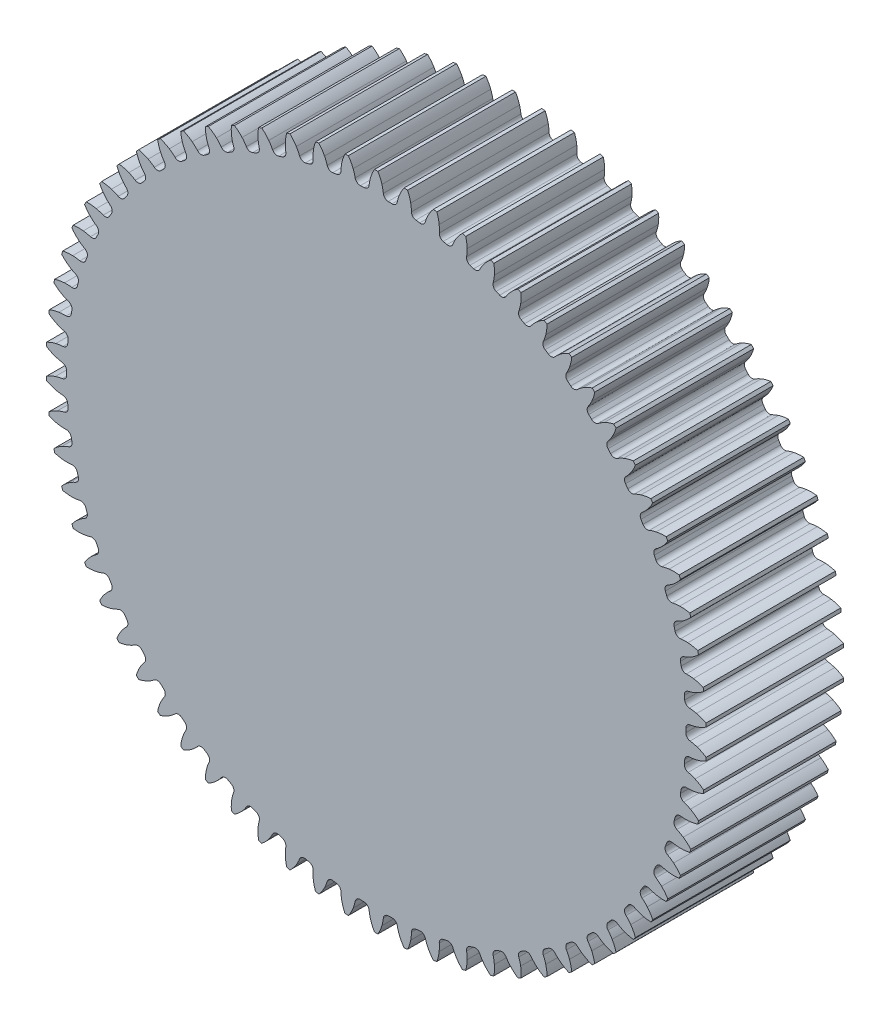
SolidWorks part; units mm, degrees
ref_plane "Front Plane" through (0, 0, 0) normal (0, 0, 1) x (1, 0, 0)
ref_plane "Top Plane" through (0, 0, 0) normal (0, 1, 0) x (1, 0, 0)
ref_plane "Right Plane" through (0, 0, 0) normal (1, 0, 0) x (0, 0, -1)
sketch "Sketch1" plane through (0, 0, 0) normal (0, 0, 1) x (1, 0, 0)
  line L0 (0, 144) -> (0, -144) construction
  circle A0 centre (0, 0) radius 140 construction
  circle A1 centre (0, 0) radius 144 construction
  arc A2 (-5.2094, 134.8995) -> (-6.9038, 134.8234) centre (0, 0) ccw
  arc A3 (-0.75, 143.998) -> (0.75, 143.998) centre (0, 0) cw
  arc A4 (0.75, 143.998) -> (2.5, 139.9777) centre (-13.7397, 135.2999) cw
  arc A5 (2.5, 139.9777) -> (3.1064, 136.8679) centre (-14.8448, 134.9815) cw
  arc A6 (3.1064, 136.8679) -> (5.2094, 134.8995) centre (5.2943, 137.0978) ccw
  arc A7 (-0.75, 143.998) -> (-2.5, 139.9777) centre (13.7397, 135.2999) ccw
  arc A8 (-2.5, 139.9777) -> (-3.1064, 136.8679) centre (14.8448, 134.9815) ccw
  arc A9 (-3.1064, 136.8679) -> (-5.2094, 134.8995) centre (-5.2943, 137.0978) cw
  arc A10 (15.3626, 136.0385) -> (17.2808, 133.8894) centre (17.5624, 136.0713) ccw
  arc A11 (15.0374, 139.1901) -> (15.3626, 136.0385) centre (-2.6854, 135.7688) cw
  arc A12 (12.1609, 143.4856) -> (13.6549, 143.3511) centre (0, 0) cw
  arc A13 (12.1609, 143.4856) -> (10.0576, 139.6383) centre (25.8126, 133.5236) ccw
  arc A14 (10.0576, 139.6383) -> (9.1749, 136.5954) centre (26.8847, 133.1075) ccw
  arc A15 (9.1749, 136.5954) -> (6.9038, 134.8234) centre (7.0163, 137.0205) cw
  arc A16 (13.6549, 143.3511) -> (15.0374, 139.1901) centre (-1.5562, 135.9868) cw
  arc A17 (27.4952, 134.1137) -> (29.213, 131.8014) centre (29.689, 133.9493) ccw
  arc A18 (27.4538, 137.2818) -> (27.4952, 134.1137) centre (9.4957, 135.463) cw
  arc A19 (24.9739, 141.8179) -> (26.4498, 141.55) centre (0, 0) cw
  arc A20 (24.9739, 141.8179) -> (22.5342, 138.1746) centre (37.6776, 130.6722) ccw
  arc A21 (22.5342, 138.1746) -> (21.3822, 135.223) centre (38.7081, 130.1617) ccw
  arc A22 (21.3822, 135.223) -> (18.9615, 133.6617) centre (19.2705, 135.8399) cw
  arc A23 (26.4498, 141.55) -> (27.4538, 137.2818) centre (10.6398, 135.5789) cw
  arc A24 (39.4063, 131.1092) -> (40.9099, 128.6522) centre (41.5766, 130.7487) ccw
  arc A25 (39.6491, 134.2682) -> (39.4063, 131.1092) centre (21.6003, 134.0665) cw
  arc A26 (37.5858, 139.0083) -> (39.0318, 138.6092) centre (0, 0) cw
  arc A27 (37.5858, 139.0083) -> (34.8293, 135.5984) centre (49.2393, 126.7688) ccw
  arc A28 (34.8293, 135.5984) -> (33.4175, 132.762) centre (50.2199, 126.1679) ccw
  arc A29 (33.4175, 132.762) -> (30.8665, 131.424) centre (31.3695, 133.5657) cw
  arc A30 (39.0318, 138.6092) -> (39.6491, 134.2682) centre (22.7502, 134.0793) cw
  arc A31 (51.0002, 127.049) -> (52.2775, 124.4671) centre (53.1295, 126.4955) ccw
  arc A32 (51.5252, 130.1735) -> (51.0002, 127.049) centre (33.5309, 131.5905) cw
  arc A33 (49.8951, 135.0795) -> (51.2995, 134.5525) centre (0, 0) cw
  arc A34 (49.8951, 135.0795) -> (46.844, 131.9304) centre (60.4046, 121.8447) ccw
  arc A35 (46.844, 131.9304) -> (45.1836, 129.232) centre (61.3273, 121.1584) ccw
  arc A36 (45.1836, 129.232) -> (42.523, 128.128) centre (43.216, 130.216) cw
  arc A37 (51.2995, 134.5525) -> (51.5252, 130.1735) centre (34.6774, 131.5002) cw
  arc A38 (62.1835, 121.9659) -> (63.2242, 119.2799) centre (64.2545, 121.2237) ccw
  arc A39 (62.9865, 125.0308) -> (62.1835, 121.9659) centre (45.1916, 128.0551) cw
  arc A40 (61.8027, 130.0632) -> (63.1541, 129.4123) centre (0, 0) cw
  arc A41 (61.8027, 130.0632) -> (58.4816, 127.2002) centre (71.0835, 115.9395) ccw
  arc A42 (58.4816, 127.2002) -> (56.586, 124.6615) centre (71.941, 115.1733) ccw
  arc A43 (56.586, 124.6615) -> (53.8371, 123.8005) centre (54.7145, 125.818) cw
  arc A44 (63.1541, 129.4123) -> (62.9865, 125.0308) centre (46.3254, 127.8624) cw
  arc A45 (72.8661, 115.9008) -> (73.6619, 113.1323) centre (74.8623, 114.976) ccw
  arc A46 (73.9406, 118.8814) -> (72.8661, 115.9008) centre (56.4885, 123.4886) cw
  arc A47 (73.2127, 123.9996) -> (74.5003, 123.2303) centre (0, 0) cw
  arc A48 (73.2127, 123.9996) -> (69.6483, 121.4459) centre (81.19, 109.1009) ccw
  arc A49 (69.6483, 121.4459) -> (67.5328, 119.0873) centre (81.9754, 108.2609) ccw
  arc A50 (67.5328, 119.0873) -> (64.7178, 118.4762) centre (65.7724, 120.4069) cw
  arc A51 (74.5003, 123.2303) -> (73.9406, 118.8814) centre (57.6004, 123.1951) cw
  arc A52 (82.9621, 108.9026) -> (83.5064, 106.0739) centre (84.8673, 107.8025) ccw
  arc A53 (84.2994, 111.7749) -> (82.9621, 108.9026) centre (67.3305, 117.9279) cw
  arc A54 (84.0332, 116.9377) -> (85.2467, 116.056) centre (0, 0) cw
  arc A55 (84.0332, 116.9377) -> (80.2543, 114.7138) centre (90.6429, 101.3839) ccw
  arc A56 (80.2543, 114.7138) -> (77.9358, 112.5543) centre (91.3498, 100.4768) ccw
  arc A57 (77.9358, 112.5543) -> (75.0774, 112.198) centre (76.3009, 114.0264) cw
  arc A58 (85.2467, 116.056) -> (84.2994, 111.7749) centre (68.4116, 117.5359) cw
  arc A59 (92.39, 101.0275) -> (92.6787, 98.1614) centre (94.189, 99.7611) ccw
  arc A60 (93.9794, 103.7683) -> (92.39, 101.0275) centre (77.6304, 111.4177) cw
  arc A61 (94.1771, 108.9343) -> (95.3067, 107.9474) centre (0, 0) cw
  arc A62 (94.1771, 108.9343) -> (90.2141, 107.058) centre (99.366, 92.8506) ccw
  arc A63 (90.2141, 107.058) -> (87.7114, 105.1151) centre (99.9888, 91.8838) ccw
  arc A64 (87.7114, 105.1151) -> (84.8325, 105.0164) centre (86.2149, 106.7278) cw
  arc A65 (95.3067, 107.9474) -> (93.9794, 103.7683) centre (78.672, 110.9303) cw
  arc A66 (101.0741, 92.339) -> (101.1047, 89.4586) centre (102.7523, 90.9165) ccw
  arc A67 (102.9028, 94.9264) -> (101.0741, 92.339) centre (87.3053, 104.0104) cw
  arc A68 (103.5628, 100.0538) -> (104.5993, 98.9696) centre (0, 0) cw
  arc A69 (103.5628, 100.0538) -> (99.4475, 98.5403) centre (107.289, 83.5697) ccw
  arc A70 (99.4475, 98.5403) -> (96.7807, 96.8296) centre (107.8226, 82.551) ccw
  arc A71 (96.7807, 96.8296) -> (93.9046, 96.9893) centre (95.4349, 98.5699) cw
  arc A72 (104.5993, 98.9696) -> (102.9028, 94.9264) centre (88.299, 103.4317) cw
  arc A73 (108.9444, 82.9071) -> (108.7167, 80.0355) centre (110.4884, 81.3398) ccw
  arc A74 (110.9977, 85.3201) -> (108.9444, 82.9071) centre (96.2773, 95.7657) cw
  arc A75 (112.1146, 90.3677) -> (113.0498, 89.1949) centre (0, 0) cw
  arc A76 (112.1146, 90.3677) -> (107.8802, 89.2292) centre (114.3483, 73.6159) ccw
  arc A77 (107.8802, 89.2292) -> (105.0708, 87.7644) centre (114.7884, 72.5535) ccw
  arc A78 (105.0708, 87.7644) -> (102.2206, 88.1813) centre (103.8864, 89.6184) cw
  arc A79 (113.0498, 89.1949) -> (110.9977, 85.3201) centre (97.2151, 95.1002) cw
  arc A80 (115.9376, 72.8076) -> (115.4533, 69.968) centre (117.3348, 71.1083) ccw
  arc A81 (118.1989, 75.0268) -> (115.9376, 72.8076) centre (104.474, 86.75) cw
  arc A82 (119.7637, 79.954) -> (120.5901, 78.7022) centre (0, 0) cw
  arc A83 (119.7637, 79.954) -> (115.4444, 79.1997) centre (120.4868, 63.0695) ccw
  arc A84 (115.4444, 79.1997) -> (112.515, 77.9926) centre (120.8299, 61.9719) ccw
  arc A85 (112.515, 77.9926) -> (109.7136, 78.6634) centre (111.5015, 79.9453) cw
  arc A86 (120.5901, 78.7022) -> (118.1989, 75.0268) centre (105.3485, 86.0031) cw
  arc A87 (121.9973, 62.1219) -> (121.2604, 59.3372) centre (123.2365, 60.3042) ccw
  arc A88 (124.4484, 64.1295) -> (121.9973, 62.1219) centre (111.8297, 77.0358) cw
  arc A89 (126.4486, 68.8966) -> (127.1594, 67.5757) centre (0, 0) cw
  arc A90 (126.4486, 68.8966) -> (122.079, 68.5325) centre (125.6553, 52.0152) ccw
  arc A91 (122.079, 68.5325) -> (119.0532, 67.5929) centre (125.8986, 50.8913) ccw
  arc A92 (119.0532, 67.5929) -> (116.3233, 68.512) centre (118.2189, 69.6285) cw
  arc A93 (127.1594, 67.5757) -> (124.4484, 64.1295) centre (112.6336, 76.2135) cw
  arc A94 (127.0747, 50.9361) -> (126.0912, 48.2286) centre (128.1461, 49.0146) ccw
  arc A95 (129.6959, 52.7159) -> (127.0747, 50.9361) centre (118.2849, 66.7013) cw
  arc A96 (132.1154, 57.2845) -> (132.705, 55.9052) centre (0, 0) cw
  arc A97 (132.1154, 57.2845) -> (127.7308, 57.3136) centre (129.812, 40.5422) ccw
  arc A98 (127.7308, 57.3136) -> (124.6329, 56.6489) centre (129.9537, 39.4009) ccw
  arc A99 (124.6329, 56.6489) -> (121.9963, 57.8091) centre (123.9844, 58.7512) cw
  arc A100 (132.705, 55.9052) -> (129.6959, 52.7159) centre (119.0119, 65.8103) cw
  arc A101 (131.129, 39.3402) -> (129.9068, 36.7317) centre (132.0238, 37.3303) ccw
  arc A102 (133.8992, 40.8778) -> (131.129, 39.3402) centre (123.7878, 55.8298) cw
  arc A103 (136.7185, 45.2111) -> (137.182, 43.7846) centre (0, 0) cw
  arc A104 (136.7185, 45.2111) -> (132.3541, 45.6331) centre (132.9236, 28.7427) ccw
  arc A105 (132.3541, 45.6331) -> (129.2092, 45.2489) centre (132.9624, 27.5934) ccw
  arc A106 (129.2092, 45.2489) -> (126.6872, 46.6407) centre (128.7517, 47.4008) cw
  arc A107 (137.182, 43.7846) -> (133.8992, 40.8778) centre (124.432, 54.8772) cw
  arc A108 (134.1276, 27.4275) -> (132.6765, 24.9391) centre (134.8386, 25.3455) ccw
  arc A109 (137.0244, 28.7106) -> (134.1276, 27.4275) centre (128.294, 44.5088) cw
  arc A110 (140.2208, 32.7738) -> (140.5546, 31.3114) centre (0, 0) cw
  arc A111 (140.2208, 32.7738) -> (135.9118, 33.5853) centre (134.965, 16.7118) ccw
  arc A112 (135.9118, 33.5853) -> (132.7451, 33.4845) centre (134.9006, 15.5636) ccw
  arc A113 (132.7451, 33.4845) -> (130.358, 35.0968) centre (132.4824, 35.6687) cw
  arc A114 (140.5546, 31.3114) -> (137.0244, 28.7106) centre (128.8502, 43.5023) cw
  arc A115 (136.0462, 15.294) -> (134.3779, 12.9457) centre (136.5677, 13.1567) ccw
  arc A116 (139.0464, 16.3123) -> (136.0462, 15.294) centre (131.7673, 32.8294) cw
  arc A117 (142.5942, 20.0725) -> (142.7955, 18.5861) centre (0, 0) cw
  arc A118 (142.5942, 20.0725) -> (138.3753, 21.267) centre (135.9197, 4.5464) ccw
  arc A119 (138.3753, 21.267) -> (135.2122, 21.4505) centre (135.7526, 3.4086) ccw
  arc A120 (135.2122, 21.4505) -> (132.9793, 23.2703) centre (135.1464, 23.6495) cw
  arc A121 (142.7955, 18.5861) -> (139.0464, 16.3123) centre (132.231, 31.7771) cw
  arc A122 (136.8694, 3.0373) -> (134.9973, 0.848) centre (137.1973, 0.8619) ccw
  arc A123 (139.9489, 3.7826) -> (136.8694, 3.0373) centre (134.1796, 20.8858) cw
  arc A124 (143.8194, 7.2097) -> (143.8867, 5.7112) centre (0, 0) cw
  arc A125 (143.8194, 7.2097) -> (139.7246, 8.7776) centre (135.7801, -7.6557) ccw
  arc A126 (139.7246, 8.7776) -> (136.5907, 9.2438) centre (135.5116, -8.7739) ccw
  arc A127 (136.5907, 9.2438) -> (134.5299, 11.2564) centre (136.7222, 11.4399) cw
  arc A128 (143.8867, 5.7112) -> (139.9489, 3.7826) centre (134.5472, 19.7961) cw
  arc A129 (136.5907, -9.2438) -> (134.5299, -11.2564) centre (136.7222, -11.4399) ccw
  arc A130 (139.7246, -8.7776) -> (136.5907, -9.2438) centre (135.5116, 8.7739) cw
  arc A131 (143.8867, -5.7112) -> (143.8194, -7.2097) centre (0, 0) cw
  arc A132 (143.8867, -5.7112) -> (139.9489, -3.7826) centre (134.5472, -19.7961) ccw
  arc A133 (139.9489, -3.7826) -> (136.8694, -3.0373) centre (134.1796, -20.8858) ccw
  arc A134 (136.8694, -3.0373) -> (134.9973, -0.848) centre (137.1973, -0.8619) cw
  arc A135 (143.8194, -7.2097) -> (139.7246, -8.7776) centre (135.7801, 7.6557) cw
  arc A136 (135.2122, -21.4505) -> (132.9793, -23.2703) centre (135.1464, -23.6495) ccw
  arc A137 (138.3753, -21.267) -> (135.2122, -21.4505) centre (135.7526, -3.4086) cw
  arc A138 (142.7955, -18.5861) -> (142.5942, -20.0725) centre (0, 0) cw
  arc A139 (142.7955, -18.5861) -> (139.0464, -16.3123) centre (132.231, -31.7771) ccw
  arc A140 (139.0464, -16.3123) -> (136.0462, -15.294) centre (131.7673, -32.8294) ccw
  arc A141 (136.0462, -15.294) -> (134.3779, -12.9457) centre (136.5677, -13.1567) cw
  arc A142 (142.5942, -20.0725) -> (138.3753, -21.267) centre (135.9197, -4.5464) cw
  arc A143 (132.7451, -33.4845) -> (130.358, -35.0968) centre (132.4824, -35.6687) ccw
  arc A144 (135.9118, -33.5853) -> (132.7451, -33.4845) centre (134.9006, -15.5636) cw
  arc A145 (140.5546, -31.3114) -> (140.2208, -32.7738) centre (0, 0) cw
  arc A146 (140.5546, -31.3114) -> (137.0244, -28.7106) centre (128.8502, -43.5023) ccw
  arc A147 (137.0244, -28.7106) -> (134.1276, -27.4275) centre (128.294, -44.5088) ccw
  arc A148 (134.1276, -27.4275) -> (132.6765, -24.9391) centre (134.8386, -25.3455) cw
  arc A149 (140.2208, -32.7738) -> (135.9118, -33.5853) centre (134.965, -16.7118) cw
  arc A150 (129.2092, -45.2489) -> (126.6872, -46.6407) centre (128.7517, -47.4008) ccw
  arc A151 (132.3541, -45.6331) -> (129.2092, -45.2489) centre (132.9624, -27.5934) cw
  arc A152 (137.182, -43.7846) -> (136.7185, -45.2111) centre (0, 0) cw
  arc A153 (137.182, -43.7846) -> (133.8992, -40.8778) centre (124.432, -54.8772) ccw
  arc A154 (133.8992, -40.8778) -> (131.129, -39.3402) centre (123.7878, -55.8298) ccw
  arc A155 (131.129, -39.3402) -> (129.9068, -36.7317) centre (132.0238, -37.3303) cw
  arc A156 (136.7185, -45.2111) -> (132.3541, -45.6331) centre (132.9236, -28.7427) cw
  arc A157 (124.6329, -56.6489) -> (121.9963, -57.8091) centre (123.9844, -58.7512) ccw
  arc A158 (127.7308, -57.3136) -> (124.6329, -56.6489) centre (129.9537, -39.4009) cw
  arc A159 (132.705, -55.9052) -> (132.1154, -57.2845) centre (0, 0) cw
  arc A160 (132.705, -55.9052) -> (129.6959, -52.7159) centre (119.0119, -65.8103) ccw
  arc A161 (129.6959, -52.7159) -> (127.0747, -50.9361) centre (118.2849, -66.7013) ccw
  arc A162 (127.0747, -50.9361) -> (126.0912, -48.2286) centre (128.1461, -49.0146) cw
  arc A163 (132.1154, -57.2845) -> (127.7308, -57.3136) centre (129.812, -40.5422) cw
  arc A164 (119.0532, -67.5929) -> (116.3233, -68.512) centre (118.2189, -69.6285) ccw
  arc A165 (122.079, -68.5325) -> (119.0532, -67.5929) centre (125.8986, -50.8913) cw
  arc A166 (127.1594, -67.5757) -> (126.4486, -68.8966) centre (0, 0) cw
  arc A167 (127.1594, -67.5757) -> (124.4484, -64.1295) centre (112.6336, -76.2135) ccw
  arc A168 (124.4484, -64.1295) -> (121.9973, -62.1219) centre (111.8297, -77.0358) ccw
  arc A169 (121.9973, -62.1219) -> (121.2604, -59.3372) centre (123.2365, -60.3042) cw
  arc A170 (126.4486, -68.8966) -> (122.079, -68.5325) centre (125.6553, -52.0152) cw
  arc A171 (112.515, -77.9926) -> (109.7136, -78.6634) centre (111.5015, -79.9453) ccw
  arc A172 (115.4444, -79.1997) -> (112.515, -77.9926) centre (120.8299, -61.9719) cw
  arc A173 (120.5901, -78.7022) -> (119.7637, -79.954) centre (0, 0) cw
  arc A174 (120.5901, -78.7022) -> (118.1989, -75.0268) centre (105.3485, -86.0031) ccw
  arc A175 (118.1989, -75.0268) -> (115.9376, -72.8076) centre (104.474, -86.75) ccw
  arc A176 (115.9376, -72.8076) -> (115.4533, -69.968) centre (117.3348, -71.1083) cw
  arc A177 (119.7637, -79.954) -> (115.4444, -79.1997) centre (120.4868, -63.0695) cw
  arc A178 (105.0708, -87.7644) -> (102.2206, -88.1813) centre (103.8864, -89.6184) ccw
  arc A179 (107.8802, -89.2292) -> (105.0708, -87.7644) centre (114.7884, -72.5535) cw
  arc A180 (113.0498, -89.1949) -> (112.1146, -90.3677) centre (0, 0) cw
  arc A181 (113.0498, -89.1949) -> (110.9977, -85.3201) centre (97.2151, -95.1002) ccw
  arc A182 (110.9977, -85.3201) -> (108.9444, -82.9071) centre (96.2773, -95.7657) ccw
  arc A183 (108.9444, -82.9071) -> (108.7167, -80.0355) centre (110.4884, -81.3398) cw
  arc A184 (112.1146, -90.3677) -> (107.8802, -89.2292) centre (114.3483, -73.6159) cw
  arc A185 (96.7807, -96.8296) -> (93.9046, -96.9893) centre (95.4349, -98.5699) ccw
  arc A186 (99.4475, -98.5403) -> (96.7807, -96.8296) centre (107.8226, -82.551) cw
  arc A187 (104.5993, -98.9696) -> (103.5628, -100.0538) centre (0, 0) cw
  arc A188 (104.5993, -98.9696) -> (102.9028, -94.9264) centre (88.299, -103.4317) ccw
  arc A189 (102.9028, -94.9264) -> (101.0741, -92.339) centre (87.3053, -104.0104) ccw
  arc A190 (101.0741, -92.339) -> (101.1047, -89.4586) centre (102.7523, -90.9165) cw
  arc A191 (103.5628, -100.0538) -> (99.4475, -98.5403) centre (107.289, -83.5697) cw
  arc A192 (87.7114, -105.1151) -> (84.8325, -105.0164) centre (86.2149, -106.7278) ccw
  arc A193 (90.2141, -107.058) -> (87.7114, -105.1151) centre (99.9888, -91.8838) cw
  arc A194 (95.3067, -107.9474) -> (94.1771, -108.9343) centre (0, 0) cw
  arc A195 (95.3067, -107.9474) -> (93.9794, -103.7683) centre (78.672, -110.9303) ccw
  arc A196 (93.9794, -103.7683) -> (92.39, -101.0275) centre (77.6304, -111.4177) ccw
  arc A197 (92.39, -101.0275) -> (92.6787, -98.1614) centre (94.189, -99.7611) cw
  arc A198 (94.1771, -108.9343) -> (90.2141, -107.058) centre (99.366, -92.8506) cw
  arc A199 (77.9358, -112.5543) -> (75.0774, -112.198) centre (76.3009, -114.0264) ccw
  arc A200 (80.2543, -114.7138) -> (77.9358, -112.5543) centre (91.3498, -100.4768) cw
  arc A201 (85.2467, -116.056) -> (84.0332, -116.9377) centre (0, 0) cw
  arc A202 (85.2467, -116.056) -> (84.2994, -111.7749) centre (68.4116, -117.5359) ccw
  arc A203 (84.2994, -111.7749) -> (82.9621, -108.9026) centre (67.3305, -117.9279) ccw
  arc A204 (82.9621, -108.9026) -> (83.5064, -106.0739) centre (84.8673, -107.8025) cw
  arc A205 (84.0332, -116.9377) -> (80.2543, -114.7138) centre (90.6429, -101.3839) cw
  arc A206 (67.5328, -119.0873) -> (64.7178, -118.4762) centre (65.7724, -120.4069) ccw
  arc A207 (69.6483, -121.4459) -> (67.5328, -119.0873) centre (81.9754, -108.2609) cw
  arc A208 (74.5003, -123.2303) -> (73.2127, -123.9996) centre (0, 0) cw
  arc A209 (74.5003, -123.2303) -> (73.9406, -118.8814) centre (57.6004, -123.1951) ccw
  arc A210 (73.9406, -118.8814) -> (72.8661, -115.9008) centre (56.4885, -123.4886) ccw
  arc A211 (72.8661, -115.9008) -> (73.6619, -113.1323) centre (74.8623, -114.976) cw
  arc A212 (73.2127, -123.9996) -> (69.6483, -121.4459) centre (81.19, -109.1009) cw
  arc A213 (56.586, -124.6615) -> (53.8371, -123.8005) centre (54.7145, -125.818) ccw
  arc A214 (58.4816, -127.2002) -> (56.586, -124.6615) centre (71.941, -115.1733) cw
  arc A215 (63.1541, -129.4123) -> (61.8027, -130.0632) centre (0, 0) cw
  arc A216 (63.1541, -129.4123) -> (62.9865, -125.0308) centre (46.3254, -127.8624) ccw
  arc A217 (62.9865, -125.0308) -> (62.1835, -121.9659) centre (45.1916, -128.0551) ccw
  arc A218 (62.1835, -121.9659) -> (63.2242, -119.2799) centre (64.2545, -121.2237) cw
  arc A219 (61.8027, -130.0632) -> (58.4816, -127.2002) centre (71.0835, -115.9395) cw
  arc A220 (45.1836, -129.232) -> (42.523, -128.128) centre (43.216, -130.216) ccw
  arc A221 (46.844, -131.9304) -> (45.1836, -129.232) centre (61.3273, -121.1584) cw
  arc A222 (51.2995, -134.5525) -> (49.8951, -135.0795) centre (0, 0) cw
  arc A223 (51.2995, -134.5525) -> (51.5252, -130.1735) centre (34.6774, -131.5002) ccw
  arc A224 (51.5252, -130.1735) -> (51.0002, -127.049) centre (33.5309, -131.5905) ccw
  arc A225 (51.0002, -127.049) -> (52.2775, -124.4671) centre (53.1295, -126.4955) cw
  arc A226 (49.8951, -135.0795) -> (46.844, -131.9304) centre (60.4046, -121.8447) cw
  arc A227 (33.4175, -132.762) -> (30.8665, -131.424) centre (31.3695, -133.5657) ccw
  arc A228 (34.8293, -135.5984) -> (33.4175, -132.762) centre (50.2199, -126.1679) cw
  arc A229 (39.0318, -138.6092) -> (37.5858, -139.0083) centre (0, 0) cw
  arc A230 (39.0318, -138.6092) -> (39.6491, -134.2682) centre (22.7502, -134.0793) ccw
  arc A231 (39.6491, -134.2682) -> (39.4063, -131.1092) centre (21.6003, -134.0665) ccw
  arc A232 (39.4063, -131.1092) -> (40.9099, -128.6522) centre (41.5766, -130.7487) cw
  arc A233 (37.5858, -139.0083) -> (34.8293, -135.5984) centre (49.2393, -126.7688) cw
  arc A234 (21.3822, -135.223) -> (18.9615, -133.6617) centre (19.2705, -135.8399) ccw
  arc A235 (22.5342, -138.1746) -> (21.3822, -135.223) centre (38.7081, -130.1617) cw
  arc A236 (26.4498, -141.55) -> (24.9739, -141.8179) centre (0, 0) cw
  arc A237 (26.4498, -141.55) -> (27.4538, -137.2818) centre (10.6398, -135.5789) ccw
  arc A238 (27.4538, -137.2818) -> (27.4952, -134.1137) centre (9.4957, -135.463) ccw
  arc A239 (27.4952, -134.1137) -> (29.213, -131.8014) centre (29.689, -133.9493) cw
  arc A240 (24.9739, -141.8179) -> (22.5342, -138.1746) centre (37.6776, -130.6722) cw
  arc A241 (9.1749, -136.5954) -> (6.9038, -134.8234) centre (7.0163, -137.0205) ccw
  arc A242 (10.0576, -139.6383) -> (9.1749, -136.5954) centre (26.8847, -133.1075) cw
  arc A243 (13.6549, -143.3511) -> (12.1609, -143.4856) centre (0, 0) cw
  arc A244 (13.6549, -143.3511) -> (15.0374, -139.1901) centre (-1.5562, -135.9868) ccw
  arc A245 (15.0374, -139.1901) -> (15.3626, -136.0385) centre (-2.6854, -135.7688) ccw
  arc A246 (15.3626, -136.0385) -> (17.2808, -133.8894) centre (17.5624, -136.0713) cw
  arc A247 (12.1609, -143.4856) -> (10.0576, -139.6383) centre (25.8126, -133.5236) cw
  arc A248 (-3.1064, -136.8679) -> (-5.2094, -134.8995) centre (-5.2943, -137.0978) ccw
  arc A249 (-2.5, -139.9777) -> (-3.1064, -136.8679) centre (14.8448, -134.9815) cw
  arc A250 (0.75, -143.998) -> (-0.75, -143.998) centre (0, 0) cw
  arc A251 (0.75, -143.998) -> (2.5, -139.9777) centre (-13.7397, -135.2999) ccw
  arc A252 (2.5, -139.9777) -> (3.1064, -136.8679) centre (-14.8448, -134.9815) ccw
  arc A253 (3.1064, -136.8679) -> (5.2094, -134.8995) centre (5.2943, -137.0978) cw
  arc A254 (-0.75, -143.998) -> (-2.5, -139.9777) centre (13.7397, -135.2999) cw
  arc A255 (-15.3626, -136.0385) -> (-17.2808, -133.8894) centre (-17.5624, -136.0713) ccw
  arc A256 (-15.0374, -139.1901) -> (-15.3626, -136.0385) centre (2.6854, -135.7688) cw
  arc A257 (-12.1609, -143.4856) -> (-13.6549, -143.3511) centre (0, 0) cw
  arc A258 (-12.1609, -143.4856) -> (-10.0576, -139.6383) centre (-25.8126, -133.5236) ccw
  arc A259 (-10.0576, -139.6383) -> (-9.1749, -136.5954) centre (-26.8847, -133.1075) ccw
  arc A260 (-9.1749, -136.5954) -> (-6.9038, -134.8234) centre (-7.0163, -137.0205) cw
  arc A261 (-13.6549, -143.3511) -> (-15.0374, -139.1901) centre (1.5562, -135.9868) cw
  arc A262 (-27.4952, -134.1137) -> (-29.213, -131.8014) centre (-29.689, -133.9493) ccw
  arc A263 (-27.4538, -137.2818) -> (-27.4952, -134.1137) centre (-9.4957, -135.463) cw
  arc A264 (-24.9739, -141.8179) -> (-26.4498, -141.55) centre (0, 0) cw
  arc A265 (-24.9739, -141.8179) -> (-22.5342, -138.1746) centre (-37.6776, -130.6722) ccw
  arc A266 (-22.5342, -138.1746) -> (-21.3822, -135.223) centre (-38.7081, -130.1617) ccw
  arc A267 (-21.3822, -135.223) -> (-18.9615, -133.6617) centre (-19.2705, -135.8399) cw
  arc A268 (-26.4498, -141.55) -> (-27.4538, -137.2818) centre (-10.6398, -135.5789) cw
  arc A269 (-39.4063, -131.1092) -> (-40.9099, -128.6522) centre (-41.5766, -130.7487) ccw
  arc A270 (-39.6491, -134.2682) -> (-39.4063, -131.1092) centre (-21.6003, -134.0665) cw
  arc A271 (-37.5858, -139.0083) -> (-39.0318, -138.6092) centre (0, 0) cw
  arc A272 (-37.5858, -139.0083) -> (-34.8293, -135.5984) centre (-49.2393, -126.7688) ccw
  arc A273 (-34.8293, -135.5984) -> (-33.4175, -132.762) centre (-50.2199, -126.1679) ccw
  arc A274 (-33.4175, -132.762) -> (-30.8665, -131.424) centre (-31.3695, -133.5657) cw
  arc A275 (-39.0318, -138.6092) -> (-39.6491, -134.2682) centre (-22.7502, -134.0793) cw
  arc A276 (-51.0002, -127.049) -> (-52.2775, -124.4671) centre (-53.1295, -126.4955) ccw
  arc A277 (-51.5252, -130.1735) -> (-51.0002, -127.049) centre (-33.5309, -131.5905) cw
  arc A278 (-49.8951, -135.0795) -> (-51.2995, -134.5525) centre (0, 0) cw
  arc A279 (-49.8951, -135.0795) -> (-46.844, -131.9304) centre (-60.4046, -121.8447) ccw
  arc A280 (-46.844, -131.9304) -> (-45.1836, -129.232) centre (-61.3273, -121.1584) ccw
  arc A281 (-45.1836, -129.232) -> (-42.523, -128.128) centre (-43.216, -130.216) cw
  arc A282 (-51.2995, -134.5525) -> (-51.5252, -130.1735) centre (-34.6774, -131.5002) cw
  arc A283 (-62.1835, -121.9659) -> (-63.2242, -119.2799) centre (-64.2545, -121.2237) ccw
  arc A284 (-62.9865, -125.0308) -> (-62.1835, -121.9659) centre (-45.1916, -128.0551) cw
  arc A285 (-61.8027, -130.0632) -> (-63.1541, -129.4123) centre (0, 0) cw
  arc A286 (-61.8027, -130.0632) -> (-58.4816, -127.2002) centre (-71.0835, -115.9395) ccw
  arc A287 (-58.4816, -127.2002) -> (-56.586, -124.6615) centre (-71.941, -115.1733) ccw
  arc A288 (-56.586, -124.6615) -> (-53.8371, -123.8005) centre (-54.7145, -125.818) cw
  arc A289 (-63.1541, -129.4123) -> (-62.9865, -125.0308) centre (-46.3254, -127.8624) cw
  arc A290 (-72.8661, -115.9008) -> (-73.6619, -113.1323) centre (-74.8623, -114.976) ccw
  arc A291 (-73.9406, -118.8814) -> (-72.8661, -115.9008) centre (-56.4885, -123.4886) cw
  arc A292 (-73.2127, -123.9996) -> (-74.5003, -123.2303) centre (0, 0) cw
  arc A293 (-73.2127, -123.9996) -> (-69.6483, -121.4459) centre (-81.19, -109.1009) ccw
  arc A294 (-69.6483, -121.4459) -> (-67.5328, -119.0873) centre (-81.9754, -108.2609) ccw
  arc A295 (-67.5328, -119.0873) -> (-64.7178, -118.4762) centre (-65.7724, -120.4069) cw
  arc A296 (-74.5003, -123.2303) -> (-73.9406, -118.8814) centre (-57.6004, -123.1951) cw
  arc A297 (-82.9621, -108.9026) -> (-83.5064, -106.0739) centre (-84.8673, -107.8025) ccw
  arc A298 (-84.2994, -111.7749) -> (-82.9621, -108.9026) centre (-67.3305, -117.9279) cw
  arc A299 (-84.0332, -116.9377) -> (-85.2467, -116.056) centre (0, 0) cw
  arc A300 (-84.0332, -116.9377) -> (-80.2543, -114.7138) centre (-90.6429, -101.3839) ccw
  arc A301 (-80.2543, -114.7138) -> (-77.9358, -112.5543) centre (-91.3498, -100.4768) ccw
  arc A302 (-77.9358, -112.5543) -> (-75.0774, -112.198) centre (-76.3009, -114.0264) cw
  arc A303 (-85.2467, -116.056) -> (-84.2994, -111.7749) centre (-68.4116, -117.5359) cw
  arc A304 (-92.39, -101.0275) -> (-92.6787, -98.1614) centre (-94.189, -99.7611) ccw
  arc A305 (-93.9794, -103.7683) -> (-92.39, -101.0275) centre (-77.6304, -111.4177) cw
  arc A306 (-94.1771, -108.9343) -> (-95.3067, -107.9474) centre (0, 0) cw
  arc A307 (-94.1771, -108.9343) -> (-90.2141, -107.058) centre (-99.366, -92.8506) ccw
  arc A308 (-90.2141, -107.058) -> (-87.7114, -105.1151) centre (-99.9888, -91.8838) ccw
  arc A309 (-87.7114, -105.1151) -> (-84.8325, -105.0164) centre (-86.2149, -106.7278) cw
  arc A310 (-95.3067, -107.9474) -> (-93.9794, -103.7683) centre (-78.672, -110.9303) cw
  arc A311 (-101.0741, -92.339) -> (-101.1047, -89.4586) centre (-102.7523, -90.9165) ccw
  arc A312 (-102.9028, -94.9264) -> (-101.0741, -92.339) centre (-87.3053, -104.0104) cw
  arc A313 (-103.5628, -100.0538) -> (-104.5993, -98.9696) centre (0, 0) cw
  arc A314 (-103.5628, -100.0538) -> (-99.4475, -98.5403) centre (-107.289, -83.5697) ccw
  arc A315 (-99.4475, -98.5403) -> (-96.7807, -96.8296) centre (-107.8226, -82.551) ccw
  arc A316 (-96.7807, -96.8296) -> (-93.9046, -96.9893) centre (-95.4349, -98.5699) cw
  arc A317 (-104.5993, -98.9696) -> (-102.9028, -94.9264) centre (-88.299, -103.4317) cw
  arc A318 (-108.9444, -82.9071) -> (-108.7167, -80.0355) centre (-110.4884, -81.3398) ccw
  arc A319 (-110.9977, -85.3201) -> (-108.9444, -82.9071) centre (-96.2773, -95.7657) cw
  arc A320 (-112.1146, -90.3677) -> (-113.0498, -89.1949) centre (0, 0) cw
  arc A321 (-112.1146, -90.3677) -> (-107.8802, -89.2292) centre (-114.3483, -73.6159) ccw
  arc A322 (-107.8802, -89.2292) -> (-105.0708, -87.7644) centre (-114.7884, -72.5535) ccw
  arc A323 (-105.0708, -87.7644) -> (-102.2206, -88.1813) centre (-103.8864, -89.6184) cw
  arc A324 (-113.0498, -89.1949) -> (-110.9977, -85.3201) centre (-97.2151, -95.1002) cw
  arc A325 (-115.9376, -72.8076) -> (-115.4533, -69.968) centre (-117.3348, -71.1083) ccw
  arc A326 (-118.1989, -75.0268) -> (-115.9376, -72.8076) centre (-104.474, -86.75) cw
  arc A327 (-119.7637, -79.954) -> (-120.5901, -78.7022) centre (0, 0) cw
  arc A328 (-119.7637, -79.954) -> (-115.4444, -79.1997) centre (-120.4868, -63.0695) ccw
  arc A329 (-115.4444, -79.1997) -> (-112.515, -77.9926) centre (-120.8299, -61.9719) ccw
  arc A330 (-112.515, -77.9926) -> (-109.7136, -78.6634) centre (-111.5015, -79.9453) cw
  arc A331 (-120.5901, -78.7022) -> (-118.1989, -75.0268) centre (-105.3485, -86.0031) cw
  arc A332 (-121.9973, -62.1219) -> (-121.2604, -59.3372) centre (-123.2365, -60.3042) ccw
  arc A333 (-124.4484, -64.1295) -> (-121.9973, -62.1219) centre (-111.8297, -77.0358) cw
  arc A334 (-126.4486, -68.8966) -> (-127.1594, -67.5757) centre (0, 0) cw
  arc A335 (-126.4486, -68.8966) -> (-122.079, -68.5325) centre (-125.6553, -52.0152) ccw
  arc A336 (-122.079, -68.5325) -> (-119.0532, -67.5929) centre (-125.8986, -50.8913) ccw
  arc A337 (-119.0532, -67.5929) -> (-116.3233, -68.512) centre (-118.2189, -69.6285) cw
  arc A338 (-127.1594, -67.5757) -> (-124.4484, -64.1295) centre (-112.6336, -76.2135) cw
  arc A339 (-127.0747, -50.9361) -> (-126.0912, -48.2286) centre (-128.1461, -49.0146) ccw
  arc A340 (-129.6959, -52.7159) -> (-127.0747, -50.9361) centre (-118.2849, -66.7013) cw
  arc A341 (-132.1154, -57.2845) -> (-132.705, -55.9052) centre (0, 0) cw
  arc A342 (-132.1154, -57.2845) -> (-127.7308, -57.3136) centre (-129.812, -40.5422) ccw
  arc A343 (-127.7308, -57.3136) -> (-124.6329, -56.6489) centre (-129.9537, -39.4009) ccw
  arc A344 (-124.6329, -56.6489) -> (-121.9963, -57.8091) centre (-123.9844, -58.7512) cw
  arc A345 (-132.705, -55.9052) -> (-129.6959, -52.7159) centre (-119.0119, -65.8103) cw
  arc A346 (-131.129, -39.3402) -> (-129.9068, -36.7317) centre (-132.0238, -37.3303) ccw
  arc A347 (-133.8992, -40.8778) -> (-131.129, -39.3402) centre (-123.7878, -55.8298) cw
  arc A348 (-136.7185, -45.2111) -> (-137.182, -43.7846) centre (0, 0) cw
  arc A349 (-136.7185, -45.2111) -> (-132.3541, -45.6331) centre (-132.9236, -28.7427) ccw
  arc A350 (-132.3541, -45.6331) -> (-129.2092, -45.2489) centre (-132.9624, -27.5934) ccw
  arc A351 (-129.2092, -45.2489) -> (-126.6872, -46.6407) centre (-128.7517, -47.4008) cw
  arc A352 (-137.182, -43.7846) -> (-133.8992, -40.8778) centre (-124.432, -54.8772) cw
  arc A353 (-134.1276, -27.4275) -> (-132.6765, -24.9391) centre (-134.8386, -25.3455) ccw
  arc A354 (-137.0244, -28.7106) -> (-134.1276, -27.4275) centre (-128.294, -44.5088) cw
  arc A355 (-140.2208, -32.7738) -> (-140.5546, -31.3114) centre (0, 0) cw
  arc A356 (-140.2208, -32.7738) -> (-135.9118, -33.5853) centre (-134.965, -16.7118) ccw
  arc A357 (-135.9118, -33.5853) -> (-132.7451, -33.4845) centre (-134.9006, -15.5636) ccw
  arc A358 (-132.7451, -33.4845) -> (-130.358, -35.0968) centre (-132.4824, -35.6687) cw
  arc A359 (-140.5546, -31.3114) -> (-137.0244, -28.7106) centre (-128.8502, -43.5023) cw
  arc A360 (-136.0462, -15.294) -> (-134.3779, -12.9457) centre (-136.5677, -13.1567) ccw
  arc A361 (-139.0464, -16.3123) -> (-136.0462, -15.294) centre (-131.7673, -32.8294) cw
  arc A362 (-142.5942, -20.0725) -> (-142.7955, -18.5861) centre (0, 0) cw
  arc A363 (-142.5942, -20.0725) -> (-138.3753, -21.267) centre (-135.9197, -4.5464) ccw
  arc A364 (-138.3753, -21.267) -> (-135.2122, -21.4505) centre (-135.7526, -3.4086) ccw
  arc A365 (-135.2122, -21.4505) -> (-132.9793, -23.2703) centre (-135.1464, -23.6495) cw
  arc A366 (-142.7955, -18.5861) -> (-139.0464, -16.3123) centre (-132.231, -31.7771) cw
  arc A367 (-136.8694, -3.0373) -> (-134.9973, -0.848) centre (-137.1973, -0.8619) ccw
  arc A368 (-139.9489, -3.7826) -> (-136.8694, -3.0373) centre (-134.1796, -20.8858) cw
  arc A369 (-143.8194, -7.2097) -> (-143.8867, -5.7112) centre (0, 0) cw
  arc A370 (-143.8194, -7.2097) -> (-139.7246, -8.7776) centre (-135.7801, 7.6557) ccw
  arc A371 (-139.7246, -8.7776) -> (-136.5907, -9.2438) centre (-135.5116, 8.7739) ccw
  arc A372 (-136.5907, -9.2438) -> (-134.5299, -11.2564) centre (-136.7222, -11.4399) cw
  arc A373 (-143.8867, -5.7112) -> (-139.9489, -3.7826) centre (-134.5472, -19.7961) cw
  arc A374 (-136.5907, 9.2438) -> (-134.5299, 11.2564) centre (-136.7222, 11.4399) ccw
  arc A375 (-139.7246, 8.7776) -> (-136.5907, 9.2438) centre (-135.5116, -8.7739) cw
  arc A376 (-143.8867, 5.7112) -> (-143.8194, 7.2097) centre (0, 0) cw
  arc A377 (-143.8867, 5.7112) -> (-139.9489, 3.7826) centre (-134.5472, 19.7961) ccw
  arc A378 (-139.9489, 3.7826) -> (-136.8694, 3.0373) centre (-134.1796, 20.8858) ccw
  arc A379 (-136.8694, 3.0373) -> (-134.9973, 0.848) centre (-137.1973, 0.8619) cw
  arc A380 (-143.8194, 7.2097) -> (-139.7246, 8.7776) centre (-135.7801, -7.6557) cw
  arc A381 (-135.2122, 21.4505) -> (-132.9793, 23.2703) centre (-135.1464, 23.6495) ccw
  arc A382 (-138.3753, 21.267) -> (-135.2122, 21.4505) centre (-135.7526, 3.4086) cw
  arc A383 (-142.7955, 18.5861) -> (-142.5942, 20.0725) centre (0, 0) cw
  arc A384 (-142.7955, 18.5861) -> (-139.0464, 16.3123) centre (-132.231, 31.7771) ccw
  arc A385 (-139.0464, 16.3123) -> (-136.0462, 15.294) centre (-131.7673, 32.8294) ccw
  arc A386 (-136.0462, 15.294) -> (-134.3779, 12.9457) centre (-136.5677, 13.1567) cw
  arc A387 (-142.5942, 20.0725) -> (-138.3753, 21.267) centre (-135.9197, 4.5464) cw
  arc A388 (-132.7451, 33.4845) -> (-130.358, 35.0968) centre (-132.4824, 35.6687) ccw
  arc A389 (-135.9118, 33.5853) -> (-132.7451, 33.4845) centre (-134.9006, 15.5636) cw
  arc A390 (-140.5546, 31.3114) -> (-140.2208, 32.7738) centre (0, 0) cw
  arc A391 (-140.5546, 31.3114) -> (-137.0244, 28.7106) centre (-128.8502, 43.5023) ccw
  arc A392 (-137.0244, 28.7106) -> (-134.1276, 27.4275) centre (-128.294, 44.5088) ccw
  arc A393 (-134.1276, 27.4275) -> (-132.6765, 24.9391) centre (-134.8386, 25.3455) cw
  arc A394 (-140.2208, 32.7738) -> (-135.9118, 33.5853) centre (-134.965, 16.7118) cw
  arc A395 (-129.2092, 45.2489) -> (-126.6872, 46.6407) centre (-128.7517, 47.4008) ccw
  arc A396 (-132.3541, 45.6331) -> (-129.2092, 45.2489) centre (-132.9624, 27.5934) cw
  arc A397 (-137.182, 43.7846) -> (-136.7185, 45.2111) centre (0, 0) cw
  arc A398 (-137.182, 43.7846) -> (-133.8992, 40.8778) centre (-124.432, 54.8772) ccw
  arc A399 (-133.8992, 40.8778) -> (-131.129, 39.3402) centre (-123.7878, 55.8298) ccw
  arc A400 (-131.129, 39.3402) -> (-129.9068, 36.7317) centre (-132.0238, 37.3303) cw
  arc A401 (-136.7185, 45.2111) -> (-132.3541, 45.6331) centre (-132.9236, 28.7427) cw
  arc A402 (-124.6329, 56.6489) -> (-121.9963, 57.8091) centre (-123.9844, 58.7512) ccw
  arc A403 (-127.7308, 57.3136) -> (-124.6329, 56.6489) centre (-129.9537, 39.4009) cw
  arc A404 (-132.705, 55.9052) -> (-132.1154, 57.2845) centre (0, 0) cw
  arc A405 (-132.705, 55.9052) -> (-129.6959, 52.7159) centre (-119.0119, 65.8103) ccw
  arc A406 (-129.6959, 52.7159) -> (-127.0747, 50.9361) centre (-118.2849, 66.7013) ccw
  arc A407 (-127.0747, 50.9361) -> (-126.0912, 48.2286) centre (-128.1461, 49.0146) cw
  arc A408 (-132.1154, 57.2845) -> (-127.7308, 57.3136) centre (-129.812, 40.5422) cw
  arc A409 (-119.0532, 67.5929) -> (-116.3233, 68.512) centre (-118.2189, 69.6285) ccw
  arc A410 (-122.079, 68.5325) -> (-119.0532, 67.5929) centre (-125.8986, 50.8913) cw
  arc A411 (-127.1594, 67.5757) -> (-126.4486, 68.8966) centre (0, 0) cw
  arc A412 (-127.1594, 67.5757) -> (-124.4484, 64.1295) centre (-112.6336, 76.2135) ccw
  arc A413 (-124.4484, 64.1295) -> (-121.9973, 62.1219) centre (-111.8297, 77.0358) ccw
  arc A414 (-121.9973, 62.1219) -> (-121.2604, 59.3372) centre (-123.2365, 60.3042) cw
  arc A415 (-126.4486, 68.8966) -> (-122.079, 68.5325) centre (-125.6553, 52.0152) cw
  arc A416 (-112.515, 77.9926) -> (-109.7136, 78.6634) centre (-111.5015, 79.9453) ccw
  arc A417 (-115.4444, 79.1997) -> (-112.515, 77.9926) centre (-120.8299, 61.9719) cw
  arc A418 (-120.5901, 78.7022) -> (-119.7637, 79.954) centre (0, 0) cw
  arc A419 (-120.5901, 78.7022) -> (-118.1989, 75.0268) centre (-105.3485, 86.0031) ccw
  arc A420 (-118.1989, 75.0268) -> (-115.9376, 72.8076) centre (-104.474, 86.75) ccw
  arc A421 (-115.9376, 72.8076) -> (-115.4533, 69.968) centre (-117.3348, 71.1083) cw
  arc A422 (-119.7637, 79.954) -> (-115.4444, 79.1997) centre (-120.4868, 63.0695) cw
  arc A423 (-105.0708, 87.7644) -> (-102.2206, 88.1813) centre (-103.8864, 89.6184) ccw
  arc A424 (-107.8802, 89.2292) -> (-105.0708, 87.7644) centre (-114.7884, 72.5535) cw
  arc A425 (-113.0498, 89.1949) -> (-112.1146, 90.3677) centre (0, 0) cw
  arc A426 (-113.0498, 89.1949) -> (-110.9977, 85.3201) centre (-97.2151, 95.1002) ccw
  arc A427 (-110.9977, 85.3201) -> (-108.9444, 82.9071) centre (-96.2773, 95.7657) ccw
  arc A428 (-108.9444, 82.9071) -> (-108.7167, 80.0355) centre (-110.4884, 81.3398) cw
  arc A429 (-112.1146, 90.3677) -> (-107.8802, 89.2292) centre (-114.3483, 73.6159) cw
  arc A430 (-96.7807, 96.8296) -> (-93.9046, 96.9893) centre (-95.4349, 98.5699) ccw
  arc A431 (-99.4475, 98.5403) -> (-96.7807, 96.8296) centre (-107.8226, 82.551) cw
  arc A432 (-104.5993, 98.9696) -> (-103.5628, 100.0538) centre (0, 0) cw
  arc A433 (-104.5993, 98.9696) -> (-102.9028, 94.9264) centre (-88.299, 103.4317) ccw
  arc A434 (-102.9028, 94.9264) -> (-101.0741, 92.339) centre (-87.3053, 104.0104) ccw
  arc A435 (-101.0741, 92.339) -> (-101.1047, 89.4586) centre (-102.7523, 90.9165) cw
  arc A436 (-103.5628, 100.0538) -> (-99.4475, 98.5403) centre (-107.289, 83.5697) cw
  arc A437 (-87.7114, 105.1151) -> (-84.8325, 105.0164) centre (-86.2149, 106.7278) ccw
  arc A438 (-90.2141, 107.058) -> (-87.7114, 105.1151) centre (-99.9888, 91.8838) cw
  arc A439 (-95.3067, 107.9474) -> (-94.1771, 108.9343) centre (0, 0) cw
  arc A440 (-95.3067, 107.9474) -> (-93.9794, 103.7683) centre (-78.672, 110.9303) ccw
  arc A441 (-93.9794, 103.7683) -> (-92.39, 101.0275) centre (-77.6304, 111.4177) ccw
  arc A442 (-92.39, 101.0275) -> (-92.6787, 98.1614) centre (-94.189, 99.7611) cw
  arc A443 (-94.1771, 108.9343) -> (-90.2141, 107.058) centre (-99.366, 92.8506) cw
  arc A444 (-77.9358, 112.5543) -> (-75.0774, 112.198) centre (-76.3009, 114.0264) ccw
  arc A445 (-80.2543, 114.7138) -> (-77.9358, 112.5543) centre (-91.3498, 100.4768) cw
  arc A446 (-85.2467, 116.056) -> (-84.0332, 116.9377) centre (0, 0) cw
  arc A447 (-85.2467, 116.056) -> (-84.2994, 111.7749) centre (-68.4116, 117.5359) ccw
  arc A448 (-84.2994, 111.7749) -> (-82.9621, 108.9026) centre (-67.3305, 117.9279) ccw
  arc A449 (-82.9621, 108.9026) -> (-83.5064, 106.0739) centre (-84.8673, 107.8025) cw
  arc A450 (-84.0332, 116.9377) -> (-80.2543, 114.7138) centre (-90.6429, 101.3839) cw
  arc A451 (-67.5328, 119.0873) -> (-64.7178, 118.4762) centre (-65.7724, 120.4069) ccw
  arc A452 (-69.6483, 121.4459) -> (-67.5328, 119.0873) centre (-81.9754, 108.2609) cw
  arc A453 (-74.5003, 123.2303) -> (-73.2127, 123.9996) centre (0, 0) cw
  arc A454 (-74.5003, 123.2303) -> (-73.9406, 118.8814) centre (-57.6004, 123.1951) ccw
  arc A455 (-73.9406, 118.8814) -> (-72.8661, 115.9008) centre (-56.4885, 123.4886) ccw
  arc A456 (-72.8661, 115.9008) -> (-73.6619, 113.1323) centre (-74.8623, 114.976) cw
  arc A457 (-73.2127, 123.9996) -> (-69.6483, 121.4459) centre (-81.19, 109.1009) cw
  arc A458 (-56.586, 124.6615) -> (-53.8371, 123.8005) centre (-54.7145, 125.818) ccw
  arc A459 (-58.4816, 127.2002) -> (-56.586, 124.6615) centre (-71.941, 115.1733) cw
  arc A460 (-63.1541, 129.4123) -> (-61.8027, 130.0632) centre (0, 0) cw
  arc A461 (-63.1541, 129.4123) -> (-62.9865, 125.0308) centre (-46.3254, 127.8624) ccw
  arc A462 (-62.9865, 125.0308) -> (-62.1835, 121.9659) centre (-45.1916, 128.0551) ccw
  arc A463 (-62.1835, 121.9659) -> (-63.2242, 119.2799) centre (-64.2545, 121.2237) cw
  arc A464 (-61.8027, 130.0632) -> (-58.4816, 127.2002) centre (-71.0835, 115.9395) cw
  arc A465 (-45.1836, 129.232) -> (-42.523, 128.128) centre (-43.216, 130.216) ccw
  arc A466 (-46.844, 131.9304) -> (-45.1836, 129.232) centre (-61.3273, 121.1584) cw
  arc A467 (-51.2995, 134.5525) -> (-49.8951, 135.0795) centre (0, 0) cw
  arc A468 (-51.2995, 134.5525) -> (-51.5252, 130.1735) centre (-34.6774, 131.5002) ccw
  arc A469 (-51.5252, 130.1735) -> (-51.0002, 127.049) centre (-33.5309, 131.5905) ccw
  arc A470 (-51.0002, 127.049) -> (-52.2775, 124.4671) centre (-53.1295, 126.4955) cw
  arc A471 (-49.8951, 135.0795) -> (-46.844, 131.9304) centre (-60.4046, 121.8447) cw
  arc A472 (-33.4175, 132.762) -> (-30.8665, 131.424) centre (-31.3695, 133.5657) ccw
  arc A473 (-34.8293, 135.5984) -> (-33.4175, 132.762) centre (-50.2199, 126.1679) cw
  arc A474 (-39.0318, 138.6092) -> (-37.5858, 139.0083) centre (0, 0) cw
  arc A475 (-39.0318, 138.6092) -> (-39.6491, 134.2682) centre (-22.7502, 134.0793) ccw
  arc A476 (-39.6491, 134.2682) -> (-39.4063, 131.1092) centre (-21.6003, 134.0665) ccw
  arc A477 (-39.4063, 131.1092) -> (-40.9099, 128.6522) centre (-41.5766, 130.7487) cw
  arc A478 (-37.5858, 139.0083) -> (-34.8293, 135.5984) centre (-49.2393, 126.7688) cw
  arc A479 (-21.3822, 135.223) -> (-18.9615, 133.6617) centre (-19.2705, 135.8399) ccw
  arc A480 (-22.5342, 138.1746) -> (-21.3822, 135.223) centre (-38.7081, 130.1617) cw
  arc A481 (-26.4498, 141.55) -> (-24.9739, 141.8179) centre (0, 0) cw
  arc A482 (-26.4498, 141.55) -> (-27.4538, 137.2818) centre (-10.6398, 135.5789) ccw
  arc A483 (-27.4538, 137.2818) -> (-27.4952, 134.1137) centre (-9.4957, 135.463) ccw
  arc A484 (-27.4952, 134.1137) -> (-29.213, 131.8014) centre (-29.689, 133.9493) cw
  arc A485 (-24.9739, 141.8179) -> (-22.5342, 138.1746) centre (-37.6776, 130.6722) cw
  arc A486 (-9.1749, 136.5954) -> (-6.9038, 134.8234) centre (-7.0163, 137.0205) ccw
  arc A487 (-10.0576, 139.6383) -> (-9.1749, 136.5954) centre (-26.8847, 133.1075) cw
  arc A488 (-13.6549, 143.3511) -> (-12.1609, 143.4856) centre (0, 0) cw
  arc A489 (-13.6549, 143.3511) -> (-15.0374, 139.1901) centre (1.5562, 135.9868) ccw
  arc A490 (-15.0374, 139.1901) -> (-15.3626, 136.0385) centre (2.6854, 135.7688) ccw
  arc A491 (-15.3626, 136.0385) -> (-17.2808, 133.8894) centre (-17.5624, 136.0713) cw
  arc A492 (-12.1609, 143.4856) -> (-10.0576, 139.6383) centre (-25.8126, 133.5236) cw
  arc A493 (6.9038, 134.8234) -> (5.2094, 134.8995) centre (0, 0) ccw
  arc A494 (18.9615, 133.6617) -> (17.2808, 133.8894) centre (0, 0) ccw
  arc A495 (30.8665, 131.424) -> (29.213, 131.8014) centre (0, 0) ccw
  arc A496 (42.523, 128.128) -> (40.9099, 128.6522) centre (0, 0) ccw
  arc A497 (53.8371, 123.8005) -> (52.2775, 124.4671) centre (0, 0) ccw
  arc A498 (64.7178, 118.4762) -> (63.2242, 119.2799) centre (0, 0) ccw
  arc A499 (75.0774, 112.198) -> (73.6619, 113.1323) centre (0, 0) ccw
  arc A500 (84.8325, 105.0164) -> (83.5064, 106.0739) centre (0, 0) ccw
  arc A501 (93.9046, 96.9893) -> (92.6787, 98.1614) centre (0, 0) ccw
  arc A502 (102.2206, 88.1813) -> (101.1047, 89.4586) centre (0, 0) ccw
  arc A503 (109.7136, 78.6634) -> (108.7167, 80.0355) centre (0, 0) ccw
  arc A504 (116.3233, 68.512) -> (115.4533, 69.968) centre (0, 0) ccw
  arc A505 (121.9963, 57.8091) -> (121.2604, 59.3372) centre (0, 0) ccw
  arc A506 (126.6872, 46.6407) -> (126.0912, 48.2286) centre (0, 0) ccw
  arc A507 (130.358, 35.0968) -> (129.9068, 36.7317) centre (0, 0) ccw
  arc A508 (132.9793, 23.2703) -> (132.6765, 24.9391) centre (0, 0) ccw
  arc A509 (134.5299, 11.2564) -> (134.3779, 12.9457) centre (0, 0) ccw
  arc A510 (134.9973, -0.848) -> (134.9973, 0.848) centre (0, 0) ccw
  arc A511 (134.3779, -12.9457) -> (134.5299, -11.2564) centre (0, 0) ccw
  arc A512 (132.6765, -24.9391) -> (132.9793, -23.2703) centre (0, 0) ccw
  arc A513 (129.9068, -36.7317) -> (130.358, -35.0968) centre (0, 0) ccw
  arc A514 (126.0912, -48.2286) -> (126.6872, -46.6407) centre (0, 0) ccw
  arc A515 (121.2604, -59.3372) -> (121.9963, -57.8091) centre (0, 0) ccw
  arc A516 (115.4533, -69.968) -> (116.3233, -68.512) centre (0, 0) ccw
  arc A517 (108.7167, -80.0355) -> (109.7136, -78.6634) centre (0, 0) ccw
  arc A518 (101.1047, -89.4586) -> (102.2206, -88.1813) centre (0, 0) ccw
  arc A519 (92.6787, -98.1614) -> (93.9046, -96.9893) centre (0, 0) ccw
  arc A520 (83.5064, -106.0739) -> (84.8325, -105.0164) centre (0, 0) ccw
  arc A521 (73.6619, -113.1323) -> (75.0774, -112.198) centre (0, 0) ccw
  arc A522 (63.2242, -119.2799) -> (64.7178, -118.4762) centre (0, 0) ccw
  arc A523 (52.2775, -124.4671) -> (53.8371, -123.8005) centre (0, 0) ccw
  arc A524 (40.9099, -128.6522) -> (42.523, -128.128) centre (0, 0) ccw
  arc A525 (29.213, -131.8014) -> (30.8665, -131.424) centre (0, 0) ccw
  arc A526 (17.2808, -133.8894) -> (18.9615, -133.6617) centre (0, 0) ccw
  arc A527 (5.2094, -134.8995) -> (6.9038, -134.8234) centre (0, 0) ccw
  arc A528 (-6.9038, -134.8234) -> (-5.2094, -134.8995) centre (0, 0) ccw
  arc A529 (-18.9615, -133.6617) -> (-17.2808, -133.8894) centre (0, 0) ccw
  arc A530 (-30.8665, -131.424) -> (-29.213, -131.8014) centre (0, 0) ccw
  arc A531 (-42.523, -128.128) -> (-40.9099, -128.6522) centre (0, 0) ccw
  arc A532 (-53.8371, -123.8005) -> (-52.2775, -124.4671) centre (0, 0) ccw
  arc A533 (-64.7178, -118.4762) -> (-63.2242, -119.2799) centre (0, 0) ccw
  arc A534 (-75.0774, -112.198) -> (-73.6619, -113.1323) centre (0, 0) ccw
  arc A535 (-84.8325, -105.0164) -> (-83.5064, -106.0739) centre (0, 0) ccw
  arc A536 (-93.9046, -96.9893) -> (-92.6787, -98.1614) centre (0, 0) ccw
  arc A537 (-102.2206, -88.1813) -> (-101.1047, -89.4586) centre (0, 0) ccw
  arc A538 (-109.7136, -78.6634) -> (-108.7167, -80.0355) centre (0, 0) ccw
  arc A539 (-116.3233, -68.512) -> (-115.4533, -69.968) centre (0, 0) ccw
  arc A540 (-121.9963, -57.8091) -> (-121.2604, -59.3372) centre (0, 0) ccw
  arc A541 (-126.6872, -46.6407) -> (-126.0912, -48.2286) centre (0, 0) ccw
  arc A542 (-130.358, -35.0968) -> (-129.9068, -36.7317) centre (0, 0) ccw
  arc A543 (-132.9793, -23.2703) -> (-132.6765, -24.9391) centre (0, 0) ccw
  arc A544 (-134.5299, -11.2564) -> (-134.3779, -12.9457) centre (0, 0) ccw
  arc A545 (-134.9973, 0.848) -> (-134.9973, -0.848) centre (0, 0) ccw
  arc A546 (-134.3779, 12.9457) -> (-134.5299, 11.2564) centre (0, 0) ccw
  arc A547 (-132.6765, 24.9391) -> (-132.9793, 23.2703) centre (0, 0) ccw
  arc A548 (-129.9068, 36.7317) -> (-130.358, 35.0968) centre (0, 0) ccw
  arc A549 (-126.0912, 48.2286) -> (-126.6872, 46.6407) centre (0, 0) ccw
  arc A550 (-121.2604, 59.3372) -> (-121.9963, 57.8091) centre (0, 0) ccw
  arc A551 (-115.4533, 69.968) -> (-116.3233, 68.512) centre (0, 0) ccw
  arc A552 (-108.7167, 80.0355) -> (-109.7136, 78.6634) centre (0, 0) ccw
  arc A553 (-101.1047, 89.4586) -> (-102.2206, 88.1813) centre (0, 0) ccw
  arc A554 (-92.6787, 98.1614) -> (-93.9046, 96.9893) centre (0, 0) ccw
  arc A555 (-83.5064, 106.0739) -> (-84.8325, 105.0164) centre (0, 0) ccw
  arc A556 (-73.6619, 113.1323) -> (-75.0774, 112.198) centre (0, 0) ccw
  arc A557 (-63.2242, 119.2799) -> (-64.7178, 118.4762) centre (0, 0) ccw
  arc A558 (-52.2775, 124.4671) -> (-53.8371, 123.8005) centre (0, 0) ccw
  arc A559 (-40.9099, 128.6522) -> (-42.523, 128.128) centre (0, 0) ccw
  arc A560 (-29.213, 131.8014) -> (-30.8665, 131.424) centre (0, 0) ccw
  arc A561 (-17.2808, 133.8894) -> (-18.9615, 133.6617) centre (0, 0) ccw
  point P990 (0, 0)
  dimension "D1" = 280
  dimension "D2" = 288
  dimension "D3" = 270
  dimension "D6" = 16.9
  dimension "D7" = 18.05
  dimension "D8" = 2.2
  dimension "D4" = 0.75
  dimension "D5" = 2.5
extrude "Boss-Extrude1" add sketch "Sketch1" along normal blind 60
